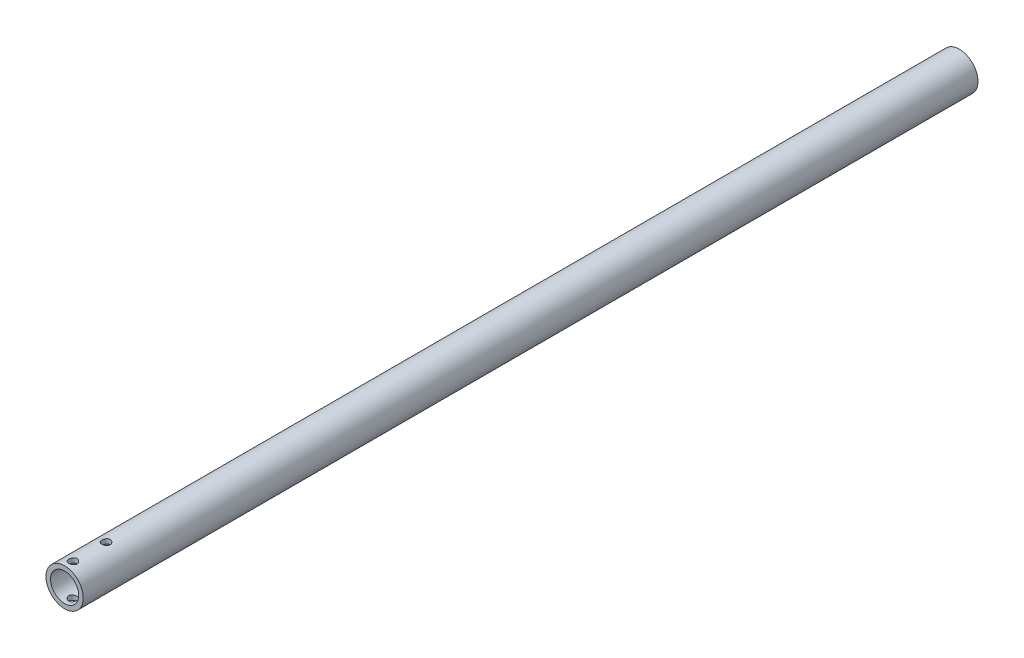
SolidWorks part; units mm, degrees
material "AISI 1020"
ref_plane "Front Plane" through (0, 0, 0) normal (0, 0, 1) x (1, 0, 0)
ref_plane "Top Plane" through (0, 0, 0) normal (0, 1, 0) x (1, 0, 0)
ref_plane "Right Plane" through (0, 0, 0) normal (1, 0, 0) x (0, 0, -1)
sketch "Sketch1" plane through (0, 0, 0) normal (0, 0, 1) x (1, 0, 0)
  circle A0 centre (0, 0) radius 14.2875
  circle A1 centre (0, 0) radius 9.525
  dimension "D1" = 28.575
  dimension "D2" = 19.05
extrude "Boss-Extrude1" add sketch "Sketch1" along normal blind 685.8 contours A0 | A1
sketch "Sketch2" plane through (0, 0, 0) normal (0, 1, 0) x (1, 0, 0)
  line L0 (0, -127) -> (0, -203.2) construction
  line L1 (7.9375, -127) -> (7.9375, -203.2)
  line L2 (-7.9375, -127) -> (-7.9375, -203.2)
  arc A0 (7.9375, -127) -> (-7.9375, -127) centre (0, -127) ccw
  arc A1 (-7.9375, -203.2) -> (7.9375, -203.2) centre (0, -203.2) ccw
  point P3 (0, -165.1)
  dimension "D1" = 203.2
  dimension "D2" = 76.2
  dimension "D3" = 15.875
extrude "Cut-Extrude1" cut sketch "Sketch2" against normal through all
sketch "Sketch3" plane through (0, 0, 685.8) normal (0, 0, 1) x (1, 0, 0)
  circle A0 centre (0, 0) radius 10.795
  circle A1 centre (0, 0) radius 14.2875
  circle A2 centre (0, 0) radius 14.2875 construction
  circle A3 centre (0, 0) radius 9.525 construction
  circle A4 centre (0, 0) radius 9.525
  dimension "D2" = 21.59
  dimension "D1" = 0
extrude "Cut-Extrude2" cut sketch "Sketch3" against normal blind 38.1
sketch "Sketch4" plane through (0, 0, 0) normal (0, 1, 0) x (1, 0, 0)
  line L0 (0, -635) -> (0, -596.9) construction
  line L1 (-8.001, -635) -> (-8.001, -596.9)
  line L2 (8.001, -635) -> (8.001, -596.9)
  line L3 (-10.795, -685.8) -> (10.795, -685.8) construction
  arc A0 (-8.001, -635) -> (8.001, -635) centre (0, -635) ccw
  arc A1 (8.001, -596.9) -> (-8.001, -596.9) centre (0, -596.9) ccw
  point P2 (0, -615.95)
  dimension "D1" = 16.002
  dimension "D2" = 38.1
  dimension "D3" = 50.8
extrude "Cut-Extrude3" cut sketch "Sketch4" against normal through all
hole_wizard "1/4 (0.25) Diameter Hole1" positions "Sketch6" profile "Sketch7" hole size "1/4" standard "ANSI Inch"
sketch "Sketch6" plane through (0, 0, 0) normal (0, 1, 0) x (1, 0, 0)
  line L0 (-14.2875, -685.8) -> (14.2875, -685.8) construction
  point P0 (0, -654.05)
  point P7 (0, -679.45)
  dimension "D1" = 31.75
  dimension "D2" = 25.4
sketch "Sketch7" plane through (0, 0, 654.05) normal (1, 0, 0) x (0, 0, -1)
  line L0 (0, 0) -> (0, 14.2875)
  line L1 (0, 14.2875) -> (3.175, 14.2875)
  line L2 (3.175, 14.2875) -> (3.175, 0)
  line L5 (3.175, 0) -> (0, 0)
  line L11 (0, -6.35) -> (0, 107.95) construction
  dimension "Thru Hole Dia." = 6.35
  dimension "Thru Hole Depth" = 14.2875
pattern_circular "CirPattern1" count 2 over 360 about axis through (0, 0, 647.7) along (0, 0, 1) of "1/4 (0.25) Diameter Hole1"
ref_plane "Plane1" through (0, 0, 25.4) normal (0, 0, 1) x (1, 0, 0)
